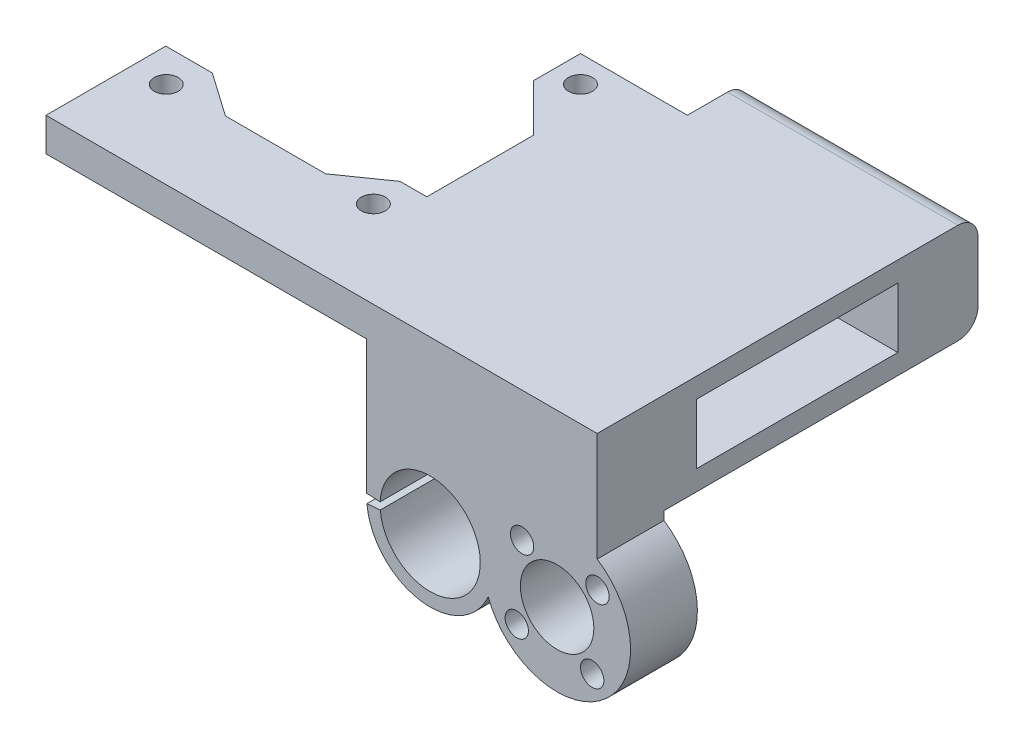
SolidWorks part; units mm, degrees
ref_plane "Front Plane" through (0, 0, 0) normal (0, 0, 1) x (1, 0, 0)
ref_plane "Top Plane" through (0, 0, 0) normal (0, 1, 0) x (1, 0, 0)
ref_plane "Right Plane" through (0, 0, 0) normal (1, 0, 0) x (0, 0, -1)
sketch "Sketch1" plane through (0, 0, 0) normal (0, 1, 0) x (1, 0, 0)
  line L0 (0, 0) -> (82.5, 0)
  line L1 (82.5, 0) -> (82.5, 57)
  line L2 (82.5, 57) -> (48, 57)
  line L3 (48, 57) -> (48, 48)
  line L4 (48, 48) -> (32, 48)
  line L5 (32, 48) -> (32, 41)
  line L6 (32, 41) -> (39.0711, 33.9289)
  line L7 (39.0711, 33.9289) -> (39.0711, 17.9289)
  line L8 (39.0711, 17.9289) -> (35.0711, 17.9289)
  line L9 (35.0711, 17.9289) -> (28.5179, 13.3403)
  line L10 (28.5179, 13.3403) -> (13.5179, 13.3403)
  line L11 (13.5179, 13.3403) -> (6.9646, 17.9289)
  line L12 (6.9646, 17.9289) -> (0, 17.9289)
  line L13 (0, 17.9289) -> (0, 0)
  line L14 (36, 44) -> (36, 13) construction
  line L15 (36, 13) -> (5, 13) construction
  circle A0 centre (5, 13) radius 1.8
  circle A1 centre (36, 13) radius 1.8
  circle A2 centre (36, 44) radius 1.8
  dimension "D16" = 3.6
  dimension "D18" = 13
  dimension "D19" = 5
  dimension "D1" = 82.5
  dimension "D2" = 57
  dimension "D3" = 34.5
  dimension "D4" = 9
  dimension "D5" = 16
  dimension "D6" = 7
  dimension "D7" = 10
  dimension "D8" = 135
  dimension "D9" = 16
  dimension "D10" = 4
  dimension "D11" = 8
  dimension "D12" = 145
  dimension "D13" = 15
  dimension "D14" = 8
  dimension "D15" = 145
  dimension "D17" = 31
extrude "Boss-Extrude1" add sketch "Sketch1" along normal blind 35 contours L12 L13 L0 L1 L2 L3 L4 L5 L6 L7 L8 L9 L10 L11 A2 A1 A0
sketch "Sketch2" plane through (0, 0, 0) normal (0, -1, 0) x (1, 0, 0)
  line L0 (82.5, -57) -> (82.5, 0)
  line L1 (82.5, 0) -> (67, 0)
  line L2 (0, 0) -> (82.5, 0) construction
  line L3 (67, 0) -> (67, -48)
  line L4 (67, -48) -> (48, -48)
  line L5 (48, -48) -> (48, -57)
  line L6 (82.5, -57) -> (48, -57) construction
  line L7 (48, -57) -> (82.5, -57)
  dimension "D1" = 15.5
extrude "Cut-Extrude1" cut sketch "Sketch2" against normal blind 20
fillet "Fillet1" radius 3 2 edges at (65.25, 35, -57) (65.25, 20, -57)
sketch "Sketch3" plane through (0, 0, -48) normal (0, 0, -1) x (-1, 0, 0)
  line L0 (-67, 0) -> (-32, 0) construction
  line L1 (-67, 20) -> (-67, 0) construction
  line L2 (-50.0285, 8.8463) -> (-48.0362, 8.672)
  line L3 (-67, 0) -> (-48, 0)
  line L4 (-67, 0) -> (-67, 20)
  line L5 (-67, 20) -> (-48, 20)
  line L6 (-48, 0) -> (-48, 20)
  line L7 (-48.013, 9.9972) -> (-50.0103, 9.8925)
  line L8 (-50.0285, 8.8463) -> (-57.5, 9.5) construction
  line L9 (-57.5, 9.5) -> (-57.5, 0) construction
  line L10 (-48.013, 9.9972) -> (-48, 9.9979)
  circle A0 centre (-57.5, 9.5) radius 9.5
  circle A1 centre (-57.5, 9.5) radius 7.5
  line M1 (-67, 0) -> (-32, 0)
  line M5 (-48, 20) -> (-67, 20)
  dimension "D1" = 19
  dimension "D2" = 15
  dimension "D3" = 8
  dimension "D4" = 85
extrude "Cut-Extrude2" cut sketch "Sketch3" against normal through all both and the other way through all contours A1 M5 | A1 M5 | A0 L4 M1 | A1 L2 A0 L7 | A0 L3 L6 | A0 L6 L10
sketch "Sketch5" plane through (0, 0, 0) normal (0, -1, 0) x (1, 0, 0)
  line L1 (48, -48) -> (0, -48)
  line L2 (48, -48) -> (48, 0)
  line L3 (48, 0) -> (0, 0)
  line L4 (0, -48) -> (0, 0)
extrude "Cut-Extrude3" cut sketch "Sketch5" against normal blind 30
sketch "Sketch6" plane through (82.5, 0, 0) normal (1, 0, 0) x (0, 0, -1)
  line L0 (45, 27.5) -> (57, 27.5) construction
  line L1 (14.858, 32) -> (45, 32)
  line L2 (14.858, 32) -> (14.858, 23)
  line L3 (14.858, 23) -> (45, 23)
  line L4 (45, 32) -> (45, 23)
  line L6 (57, 32) -> (57, 23) construction
  dimension "D1" = 9
  dimension "D2" = 30.142
  dimension "D3" = 12
extrude "Cut-Extrude4" cut sketch "Sketch6" against normal blind 31.4
sketch "Sketch7" plane through (51.1, 0, 0) normal (1, 0, 0) x (0, 0, -1)
  line L0 (14.858, 23) -> (45, 23) construction
  line L3 (17.9289, 23) -> (38.9289, 23)
  line L4 (17.9289, 23) -> (17.9289, 32)
  line L7 (17.9289, 32) -> (38.9289, 32)
  line L8 (38.9289, 23) -> (38.9289, 32)
  line L9 (45, 32) -> (14.858, 32) construction
  dimension "D1" = 21
extrude "Cut-Extrude5" cut sketch "Sketch7" against normal through all
sketch "Sketch8" plane through (0, 30, 0) normal (0, -1, 0) x (1, 0, 0)
  circle A0 centre (5, -13) radius 3.5
  circle A1 centre (36, -13) radius 3.5
  circle A2 centre (36, -44) radius 3.5
  dimension "D1" = 7
extrude "Cut-Extrude6" cut sketch "Sketch8" against normal blind 1.5
sketch "Sketch11" plane through (0, 0, 0) normal (0, 0, 1) x (1, 0, 0)
  line L0 (76.5, 9.5) -> (57.5, 9.5) construction
  line L1 (65.5, 9.5) -> (65.5, 20.5)
  line L2 (65.5, 20.5) -> (76.5, 20.5)
  line L3 (76.5, 9.5) -> (76.5, 17.5) construction
  line L4 (82.5377, 14.7485) -> (70.4623, 4.2515) construction
  line L5 (71.2515, 15.5377) -> (81.7485, 3.4623) construction
  line L6 (82.5, 20) -> (82.5, 18.7195)
  circle A0 centre (76.5, 9.5) radius 11
  circle A1 centre (76.5, 9.5) radius 5.5
  circle A2 centre (76.5, 9.5) radius 8 construction
  circle A3 centre (82.5377, 14.7485) radius 1.75
  circle A4 centre (81.7485, 3.4623) radius 1.75
  circle A5 centre (70.4623, 4.2515) radius 1.75
  circle A6 centre (71.2515, 15.5377) radius 1.75
  arc M10 (48.0362, 8.672) -> (67, 9.5) centre (57.5, 9.5) ccw
  line M11 (67, 9.5) -> (67, 20)
  line M12 (67, 20) -> (82.5, 20)
  dimension "D1" = 22
  dimension "D3" = 11
  dimension "D4" = 16
  dimension "D6" = 3.5
  dimension "D2" = 19
  dimension "D5" = 41
extrude "Boss-Extrude3" add sketch "Sketch11" against normal blind 10 contours A6 A0 M12 M11 | A6 A0 A5 A4 A3 A1 M11 M10 M12 | A0 L6 M12
